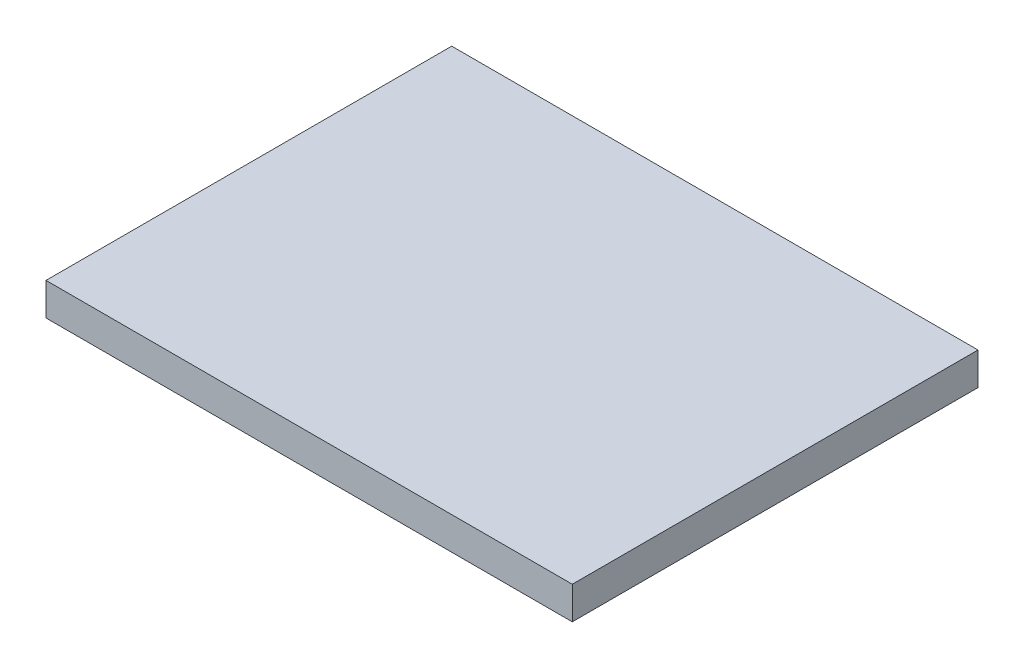
SolidWorks part; units mm, degrees
material "Klon"
ref_plane "Płaszczyzna przednia" through (0, 0, 0) normal (0, 0, 1) x (1, 0, 0)
ref_plane "Płaszczyzna górna" through (0, 0, 0) normal (0, 1, 0) x (1, 0, 0)
ref_plane "Płaszczyzna prawa" through (0, 0, 0) normal (1, 0, 0) x (0, 0, -1)
sketch "Szkic1" plane through (0, 0, 0) normal (0, 1, 0) x (1, 0, 0)
  line L1 (-161.5, -124.5) -> (161.5, -124.5)
  line L2 (-161.5, -124.5) -> (-161.5, 124.5)
  line L3 (-161.5, 124.5) -> (161.5, 124.5)
  line L4 (161.5, -124.5) -> (161.5, 124.5)
  line L5 (-161.5, -124.5) -> (161.5, 124.5) construction
  line L6 (-161.5, 124.5) -> (161.5, -124.5) construction
  point P0 (0, 0)
  dimension "D1" = 323
  dimension "D2" = 249
extrude "Dodanie-wyciągnięcie1" add sketch "Szkic1" along normal blind 20
